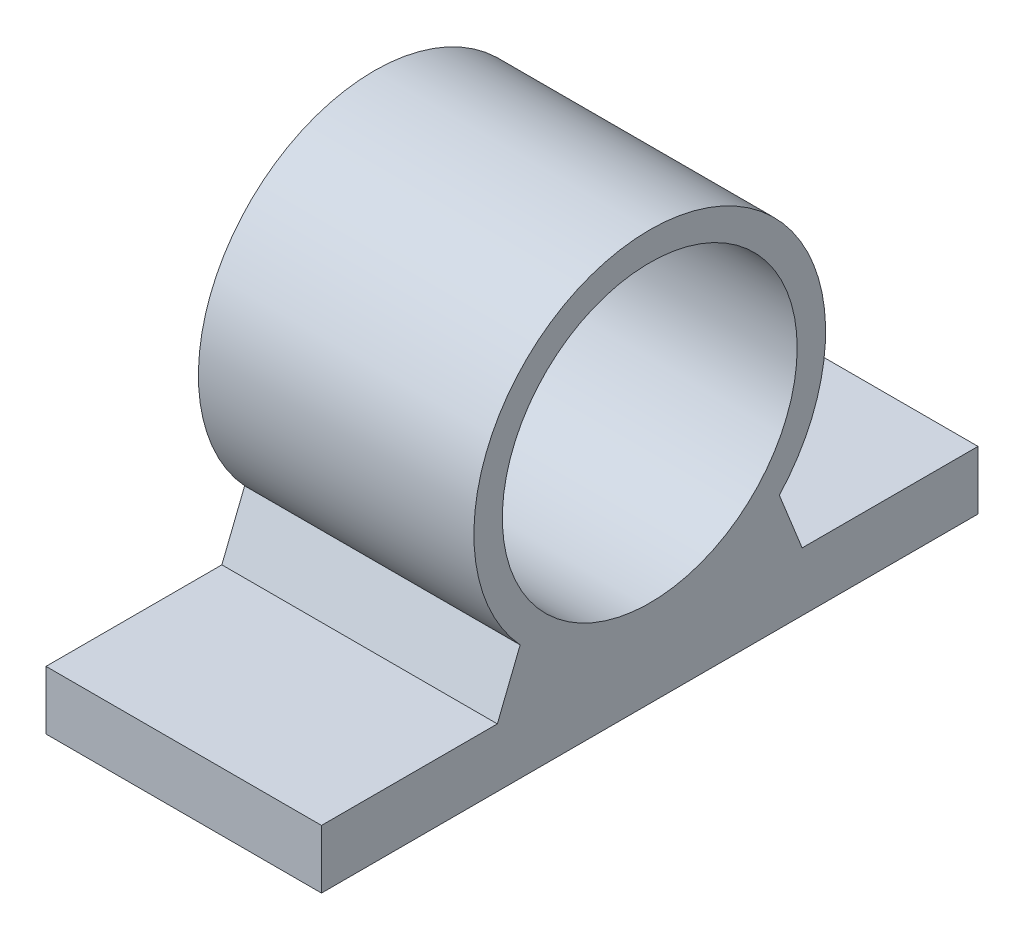
SolidWorks part; units mm, degrees
material "ABS PC"
ref_plane "Alzado" through (0, 0, 0) normal (0, 0, 1) x (1, 0, 0)
ref_plane "Planta" through (0, 0, 0) normal (0, 1, 0) x (1, 0, 0)
ref_plane "Vista lateral" through (0, 0, 0) normal (1, 0, 0) x (0, 0, -1)
sketch "Croquis1" plane through (0, 0, 0) normal (1, 0, 0) x (0, 0, -1)
  line L0 (-110, 24.5) -> (-110, 15) construction
  line L1 (125, -2.5) -> (-125, -2.5)
  line L2 (125, -2.5) -> (125, 2.5)
  line L3 (125, 2.5) -> (-97, 2.5)
  line L4 (-125, -2.5) -> (-125, 2.5)
  line L5 (125, -2.5) -> (0, 0) construction
  line L6 (125, 2.5) -> (-125, -2.5) construction
  line L7 (-117, 17.5) -> (-123, 2.5)
  line L8 (-103, 17.5) -> (-97, 2.5)
  line L9 (-123, 2.5) -> (-125, 2.5)
  circle A0 centre (-110, 17.5) radius 2.5
  arc A1 (-103, 17.5) -> (-117, 17.5) centre (-110, 17.5) ccw
  point P0 (0, 0)
  dimension "D1" = 250
  dimension "D3" = 5
  dimension "D4" = 14
  dimension "D2" = 5
  dimension "D5" = 15
  dimension "D6" = 15
  dimension "D7" = 2
extrude "Saliente-Extruir1" add sketch "Croquis1" along normal mid plane 2.5
sketch "Croquis5" plane through (1.25, 0, 0) normal (1, 0, 0) x (0, 0, -1)
  line L5 (-117, 17.5) -> (-123, 2.5)
  line L6 (-123, 2.5) -> (-125, 2.5)
  line L7 (-125, -2.5) -> (125, -2.5)
  line L8 (125, -2.5) -> (125, 2.5)
  line L9 (-97, 2.5) -> (-103, 17.5)
  line L10 (-117, 17.5) -> (-123, 2.5)
  line L12 (-125, -2.5) -> (125, -2.5)
  line L14 (-97, 2.5) -> (-103, 17.5)
  line L16 (-123, 2.5) -> (-125, 2.5)
  line L17 (-125, 2.5) -> (-125, -2.5)
  line L18 (-125, 2.5) -> (-125, -2.5)
  line L20 (125, -2.5) -> (125, 2.5)
  line L21 (125, 2.5) -> (-97, 2.5)
  line L22 (125, 2.5) -> (-97, 2.5)
  circle A0 centre (-110, 17.5) radius 12.5
  arc A1 (-103, 17.5) -> (-117, 17.5) centre (-110, 17.5) ccw
  arc A2 (-103, 17.5) -> (-117, 17.5) centre (-110, 17.5) ccw
  circle A3 centre (-110, 17.5) radius 15
  dimension "D2" = 25
  dimension "D3" = 30
  dimension "D1" = 0
extrude "Saliente-Extruir4" add sketch "Croquis5" against normal through all contours L14 A3 L10 A0
sketch "Croquis6" plane through (1.25, 0, 0) normal (1, 0, 0) x (0, 0, -1)
  circle A0 centre (-110, 17.5) radius 12.575
  dimension "D1" = 25.15
extrude "Cortar-Extruir3" cut sketch "Croquis6" against normal blind 10
sketch "Croquis7" plane through (0, 0, -125) normal (0, 0, -1) x (-1, 0, 0)
  line L0 (1.25, 32.75) -> (-1.25, 32.75)
  line L1 (1.25, -2.5) -> (3.75, -2.5)
  line L2 (1.25, -2.5) -> (1.25, 2.5) construction
  line L3 (-1.25, 2.5) -> (1.25, 2.5) construction
  line L4 (1.25, -2.5) -> (1.25, 2.5)
  line L5 (-1.25, 2.5) -> (1.25, 2.5)
  line L6 (1.25, 2.5) -> (1.25, 32.75)
  line L7 (1.25, 7.3619) -> (1.25, 32.5) construction
  line L9 (-1.25, 32.75) -> (-1.25, 37.75)
  line L10 (-1.25, 37.75) -> (3.75, 37.75)
  line L11 (3.75, 37.75) -> (3.75, -2.5)
  line M2 (1.25, -2.5) -> (1.25, 2.5)
  dimension "D1" = 30.25
  dimension "D2" = 5
  dimension "D3" = 2.5
extrude "Saliente-Extruir5" add sketch "Croquis7" against normal blind 200 contours L11 L10 L9 L0 L6 L1 M2
sketch "Croquis8" plane through (-1.25, 0, 0) normal (-1, 0, 0) x (0, 0, 1)
  line L0 (97, 2.5) -> (95, 2.5)
  line L1 (75, 2.5) -> (97, 2.5) construction
  line L2 (95, 2.5) -> (95, -2.5)
  line L3 (125, -2.5) -> (75, -2.5) construction
  line L11 (75, 2.5) -> (75, -2.5)
  line L12 (75, -2.5) -> (125, -2.5)
  line L13 (125, -2.5) -> (125, 2.5)
  line L14 (125, 2.5) -> (123, 2.5)
  line L15 (123, 2.5) -> (121.0552, 7.3619)
  line L16 (98.9448, 7.3619) -> (97, 2.5)
  line L17 (97, 2.5) -> (75, 2.5)
  line L18 (75, 2.5) -> (75, -2.5)
  line L19 (75, -2.5) -> (125, -2.5)
  line L20 (125, -2.5) -> (125, 2.5)
  line L21 (125, 2.5) -> (123, 2.5)
  line L22 (123, 2.5) -> (121.0552, 7.3619)
  line L23 (98.9448, 7.3619) -> (97, 2.5)
  line L24 (97, 2.5) -> (75, 2.5)
  circle A0 centre (110, 17.5) radius 12.575 construction
  arc A1 (121.0552, 7.3619) -> (98.9448, 7.3619) centre (110, 17.5) ccw
  arc A2 (121.0552, 7.3619) -> (98.9448, 7.3619) centre (110, 17.5) ccw
  circle A3 centre (110, 17.5) radius 12.575
  circle M2 centre (110, 17.5) radius 12.575
  line M4 (75, -2.5) -> (125, -2.5)
  line M5 (125, -2.5) -> (125, 2.5)
  line M6 (125, 2.5) -> (123, 2.5)
  line M7 (123, 2.5) -> (121.0552, 7.3619)
  arc M8 (121.0552, 7.3619) -> (98.9448, 7.3619) centre (110, 17.5) ccw
  line M9 (98.9448, 7.3619) -> (97, 2.5)
  line M10 (97, 2.5) -> (75, 2.5)
  dimension "D1" = 2
  dimension "D2" = 0
extrude "Saliente-Extruir6" add sketch "Croquis8" along normal blind 21 contours L2 M10 M4 M5 M6 M7 M8 M9 M2
sketch "Croquis9" plane through (1.25, 0, 0) normal (1, 0, 0) x (0, 0, -1)
  line L0 (-97, 2.5) -> (-97, -2.5)
  line L1 (-123, 2.5) -> (-123, -2.5)
  line L2 (-75, 32.75) -> (-75, 2.5) construction
  line L3 (-75, 2.5) -> (125, 2.5) construction
  line L4 (125, 2.5) -> (125, 32.75) construction
  line L5 (125, 32.75) -> (-75, 32.75) construction
  line L6 (125, 32.75) -> (125, 37.75) construction
  line L7 (-123, 2.5) -> (-125, 2.5)
  line L8 (-125, 2.5) -> (-125, -2.5)
  line L9 (-125, -2.5) -> (125, -2.5)
  line L10 (125, -2.5) -> (125, 2.5)
  line L11 (125, 2.5) -> (-97, 2.5)
  line L12 (-97, 2.5) -> (-98.9448, 7.3619)
  line L13 (-121.0552, 7.3619) -> (-123, 2.5)
  line L14 (-123, 2.5) -> (-125, 2.5)
  line L15 (-125, 2.5) -> (-125, -2.5)
  line L16 (-125, -2.5) -> (125, -2.5)
  line L17 (125, -2.5) -> (125, 2.5)
  line L18 (125, 2.5) -> (-97, 2.5)
  line L19 (-97, 2.5) -> (-98.9448, 7.3619)
  line L20 (-121.0552, 7.3619) -> (-123, 2.5)
  line L21 (125, 37.75) -> (-75, 37.75) construction
  line L22 (-75, 37.75) -> (-75, 32.75) construction
  line L23 (-75, 32.75) -> (125, 32.75) construction
  line L24 (-75, 32.75) -> (-75, 2.5)
  line L25 (-75, 2.5) -> (125, 2.5)
  line L26 (125, 2.5) -> (125, 32.75)
  line L27 (125, 32.75) -> (-75, 32.75)
  line L28 (125, 32.75) -> (125, 37.75)
  line L29 (125, 37.75) -> (-75, 37.75)
  line L30 (-75, 37.75) -> (-75, 32.75)
  line L31 (-75, 32.75) -> (125, 32.75)
  arc A1 (-98.9448, 7.3619) -> (-121.0552, 7.3619) centre (-110, 17.5) ccw
  arc A2 (-98.9448, 7.3619) -> (-121.0552, 7.3619) centre (-110, 17.5) ccw
  line M18 (-123, 2.5) -> (-125, 2.5)
  line M19 (-125, 2.5) -> (-125, -2.5)
  line M20 (-125, -2.5) -> (125, -2.5)
  line M21 (125, -2.5) -> (125, 2.5)
  line M22 (125, 2.5) -> (-97, 2.5)
  dimension "D1" = 0
extrude "Cortar-Extruir6" cut sketch "Croquis9" against normal through all contours L18 L0 M22 M20 M21 | L26 L27 L24 M22 | L29 L30 L27 L28 | L1 M18 M19 M20
sketch "Croquis10" plane through (0, 0, 97) normal (0, 0, -1) x (-1, 0, 0)
  line L4 (-1.25, 2.5) -> (-1.25, -2.5)
  line L5 (-1.25, -2.5) -> (22.25, -2.5)
  line L6 (22.25, -2.5) -> (22.25, 2.5)
  line L7 (22.25, 2.5) -> (-1.25, 2.5)
  line L8 (-1.25, 2.5) -> (-1.25, -2.5)
  line L9 (-1.25, -2.5) -> (22.25, -2.5)
  line L10 (22.25, -2.5) -> (22.25, 2.5)
  line L11 (22.25, 2.5) -> (-1.25, 2.5)
  dimension "D1" = 0
extrude "Saliente-Extruir7" add sketch "Croquis10" along normal blind 15
sketch "Croquis11" plane through (0, 0, 123) normal (0, 0, 1) x (1, 0, 0)
  line L4 (1.25, -2.5) -> (1.25, 2.5)
  line L5 (1.25, 2.5) -> (-22.25, 2.5)
  line L6 (-22.25, 2.5) -> (-22.25, -2.5)
  line L7 (-22.25, -2.5) -> (1.25, -2.5)
  line L8 (1.25, -2.5) -> (1.25, 2.5)
  line L9 (1.25, 2.5) -> (-22.25, 2.5)
  line L10 (-22.25, 2.5) -> (-22.25, -2.5)
  line L11 (-22.25, -2.5) -> (1.25, -2.5)
  dimension "D1" = 0
extrude "Saliente-Extruir8" add sketch "Croquis11" along normal blind 15
